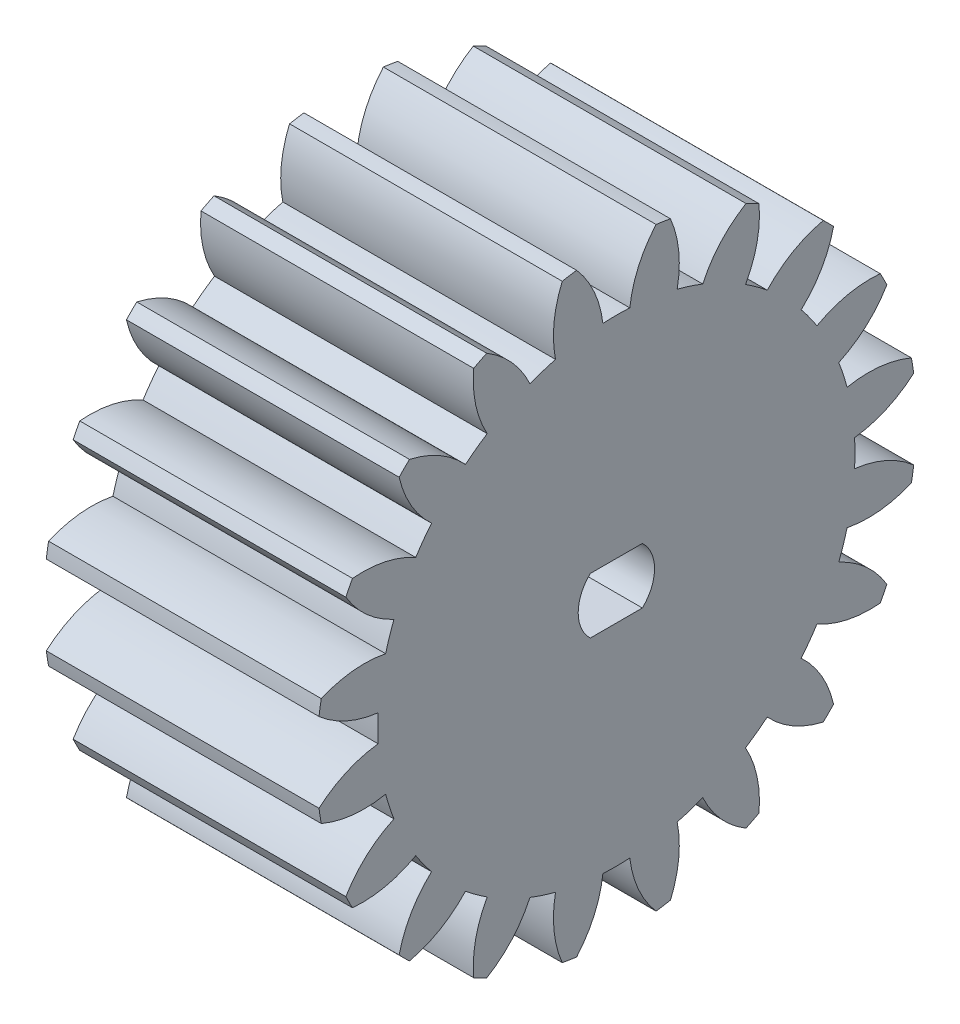
SolidWorks part; units mm, degrees
material "Delrin 2700 NC010, Low Viscosity Acetal Copolymer (SS)"
ref_plane "Plane1" through (0, 0, 0) normal (0, 0, 1) x (1, 0, 0)
ref_plane "Plane2" through (0, 0, 0) normal (0, 1, 0) x (1, 0, 0)
ref_plane "Plane3" through (0, 0, 0) normal (1, 0, 0) x (0, 0, -1)
sketch "HoldingSke" plane through (0, 0, 0) normal (0, 1, 0) x (1, 0, 0)
  line L0 (0, 0) -> (0.4698, -0.171)
  line L1 (-15, 0) -> (100, 0) construction
  line L2 (0, 0) -> (-2.1039, 2.3779)
  line L3 (0, 0) -> (-11.863, 4.5341)
  line L4 (0, 0) -> (8.1152, 2.9537)
  line L5 (0, 0) -> (-46.8476, -17.4728)
  line L6 (0, 0) -> (-4.1448, -2.7965)
  line L7 (-2.1039, 2.3779) -> (8.6586, 51.2059)
  line L8 (-76.2, 54.61) -> (-76.1, 54.61)
  line L9 (-71.009, 38.7566) -> (-53.1078, 45.2721)
  line L10 (-76.2, 71.12) -> (104.1128, 71.12)
  line L11 (0, 0) -> (-5, 0)
  line L12 (-76.2, 101.6) -> (-76.133, 101.6)
  line L13 (24.9733, 27.94) -> (52.9518, 28.4284)
  line L14 (24.9733, 27.94) -> (24.9743, 27.94)
  line L15 (24.9733, 27.94) -> (100.4006, 29.5858)
  line L16 (-63.627, -2) -> (-12.827, -2)
  circle A0 centre (0, 0) radius 0.4
  circle A1 centre (0, 0) radius 17.499
  circle A2 centre (0, 0) radius 37.5
  circle A3 centre (0, 0) radius 0.4
  dimension "MHD" = 34.998
  dimension "Hub_dia" = 75
  dimension "Bore" = 0.8
  dimension "MBD" = 0.8
  dimension "Num_teeth" = 20
  dimension "Pitch" = 0.5
  dimension "Overall_len" = 50
  dimension "Show_teeth" = 20
  dimension "Thickness" = 5
  dimension "OAL" = 50.0001
  dimension "T_dim" = 0.1
  dimension "Ap" = 20
  dimension "H" = 19.05
  dimension "Pitch_radius" = 180.3128
  dimension "Width" = 5
  dimension "Backlash" = 0.067
  dimension "Addendum_fac" = 1
  dimension "Dedendum_fac" = 1.25
  dimension "Clearance_fac" = 0.25
  dimension "Dedendum_add" = 0.001
  dimension "Module" = 2
sketch "BasProSke" plane through (0, 0, 0) normal (0, 1, 0) x (1, 0, 0)
  line L0 (-10, 0) -> (60, 0) construction
  line L1 (0, 0) -> (0, 22)
  line L2 (0, 0) -> (20, 0)
  line L3 (20, 0) -> (20, 22)
  line L4 (20, 22) -> (0, 22)
  dimension "Thickness" = 20
  dimension "Diameter" = 44
revolve "Base-Revolve" add sketch "BasProSke" angle 360 about L0
sketch "TooCutSke" plane through (0, 0, 0) normal (1, 0, 0) x (0, 0, -1)
  line L1 (0, 0) -> (0, 107) construction
  line L2 (0, 0) -> (-1.6864, 19.9288) construction
  line L3 (0, 0) -> (-6.2409, 39.4033) construction
  line L4 (-1.6864, 19.9288) -> (-3.1204, 19.7016) construction
  arc A0 (0.9862, 17.4712) -> (-0.9862, 17.4712) centre (0, 0) ccw
  arc A1 (2.9329, 21.8293) -> (-2.9329, 21.8293) centre (0, 0) ccw
  circle A2 centre (0, 0) radius 20 construction
  circle A3 centre (0, 0) radius 18.7939 construction
  arc A4 (-0.9862, 17.4712) -> (-2.9329, 21.8293) centre (-8.9313, 16.536) ccw
  arc A5 (2.9329, 21.8293) -> (0.9862, 17.4712) centre (8.9313, 16.536) ccw
  dimension "Root_dia" = 34.998
  dimension "Overcut_dia" = 44.0508
  dimension "Pitch_dia" = 40
  dimension "Base_dia" = 37.5877
  dimension "Flank_rad" = 8
  dimension "Half_ang" = 9
  dimension "Half_CT" = 1.4519
extrude "ToothCut" cut sketch "TooCutSke" along normal through all
fillet "Breaks" [suppressed] radius 0.04
fillet "RootFillets" [suppressed] radius 0.501
pattern_circular "TeethCuts" count 20 every 18 about axis through (-10, 0, 0) along (1, 0, 0) of "ToothCut", "RootFillets", "Breaks"
sketch "HubNeaOneSke" plane through (0, 0, 0) normal (-1, 0, 0) x (0, 0, 1)
  circle A0 centre (0, 0) radius 17.499
  dimension "Diameter" = 34.998
extrude "HubNearOne" [suppressed] add sketch "HubNeaOneSke" along normal blind 30.0001
sketch "HubNeaBotSke" plane through (0, 0, 0) normal (-1, 0, 0) x (0, 0, 1)
  circle A0 centre (0, 0) radius 17.499
  dimension "Diameter" = 34.998
extrude "HubNearBoth" [suppressed] add sketch "HubNeaBotSke" along normal blind 15
ref_plane "FarPln" through (20, 0, 0) normal (1, 0, 0) x (0, 0, -1)
sketch "HubFarSke" plane through (20, 0, 0) normal (1, 0, 0) x (0, 0, -1)
  circle A0 centre (0, 0) radius 17.499
  dimension "Diameter" = 34.998
extrude "HubFar" [suppressed] add sketch "HubFarSke" along normal blind 15
sketch "BorSke" plane through (0, 0, 0) normal (1, 0, 0) x (0, 0, -1)
  circle A0 centre (0, 0) radius 0.4
  dimension "Diameter" = 0.8
extrude "Bore" [suppressed] cut sketch "BorSke" along normal mid plane 100.0001
sketch "KeySke" plane through (0, 0, 0) normal (1, 0, 0) x (0, 0, -1)
  line L0 (-0.05, 0) -> (-0.05, 0.5)
  line L1 (-0.05, 0.5) -> (0.05, 0.5)
  line L2 (0.05, 0.5) -> (0.05, 0)
  line L3 (0, 0) -> (0, 34) construction
  line L4 (-0.05, 0) -> (0.05, 0)
  dimension "Offset" = 0.5
  dimension "Width" = 0.1
extrude "Keyway" [suppressed] cut sketch "KeySke" along normal mid plane 100.0001
pattern_circular "Keyway2" [suppressed] count 2 every 90 about axis through (-10, 0, 0) along (1, 0, 0)
sketch "Sketch1" plane through (20, 0, 0) normal (1, 0, 0) x (0, 0, -1)
  line L0 (-1.9072, 2.05) -> (1.9072, 2.05)
  line L1 (-1.9072, -2.05) -> (1.9072, -2.05)
  circle A0 centre (0, 0) radius 2.8
  dimension "D1" = 5.6
  dimension "D2" = 2.05
  dimension "D3" = 2.05
extrude "Cut-Extrude1" cut sketch "Sketch1" against normal through all contours L0 A0 L1
equation "' \"Module@HoldingSke\" = 6.35"
equation "' \"Num_teeth@HoldingSke\" = 12"
equation "' \"Ap@HoldingSke\" =  20"
equation "' \"Ap@HoldingSke\" = 20"
equation "' \"Width@HoldingSke\" = 0.5 * 25.4"
equation "' \"Hub_dia@HoldingSke\"= 1 * 25.4"
equation "' \"Hub_dia@HoldingSke\" = 1 * 25.4"
equation "' \"Overall_len@HoldingSke\" = 1.0 * 25.4"
equation "' \"Bore@HoldingSke\" = 0.75 * 25.4"
equation "' \"T_dim@HoldingSke\" = 0.1 * 25.4"
equation "' \"Width@KeySke\" = 0.25 * 25.4"
equation "' \"Show_teeth@HoldingSke\" = 13"
equation "' \"Backlash@HoldingSke\" = 0.009 * 25.4"
equation "' \"Addendum_fac@HoldingSke\" = 1.0"
equation "' \"Dedendum_fac@HoldingSke\" = 1.25"
equation "' \"Dedendum_add@HoldingSke\" = 0.00005 * 25.4"
equation "' \"Clearance_fac@HoldingSke\" = 0.25"
equation "\"Pitch@HoldingSke\" = 1 / \"Module@HoldingSke\""
equation "\"Overcut_dia@TooCutSke\" = (\"Num_teeth@HoldingSke\" + 2 * \"Addendum_fac@HoldingSke\") / \"Pitch@HoldingSke\" + 0.002 * 25.4"
equation "\"Pitch_dia@TooCutSke\" = \"Num_teeth@HoldingSke\" / \"Pitch@HoldingSke\""
equation "\"Base_dia@TooCutSke\" = \"Num_teeth@HoldingSke\" / \"Pitch@HoldingSke\" * cos((\"Ap@HoldingSke\"  * 3.14159265 / 180))"
equation "\"Root_dia@TooCutSke\" = (\"Num_teeth@HoldingSke\" + 2) / \"Pitch@HoldingSke\" - 2 * (\"Addendum_fac@HoldingSke\" + \"Dedendum_fac@HoldingSke\") / \"Pitch@HoldingSke\" - \"Dedendum_add@HoldingSke\" * 2"
equation "\"Half_ang@TooCutSke\" = 180 / \"Num_teeth@HoldingSke\""
equation "\"Half_CT@TooCutSke\" = \"Num_teeth@HoldingSke\" / \"Pitch@HoldingSke\" * sin((3.14159265 / 2 / \"Num_teeth@HoldingSke\")) / 2 - 7 * \"Backlash@HoldingSke\" / 4"
equation "\"Flank_rad@TooCutSke\" = \"Num_teeth@HoldingSke\" / \"Pitch@HoldingSke\" / 5"
equation "\"Radius@RootFillets\" = \"Clearance_fac@HoldingSke\" / \"Pitch@HoldingSke\" + \"Dedendum_add@HoldingSke\""
equation "\"Break_rad@Breaks\" = 0.02 / \"Pitch@HoldingSke\""
equation "\"Thickness@HoldingSke\" = \"Width@HoldingSke\""
equation "\"OAL@HoldingSke\" = \"Thickness@HoldingSke\""
equation "\"MHD@HoldingSke\" = (\"Num_teeth@HoldingSke\" + 2) / \"Pitch@HoldingSke\" - 2 * (\"Addendum_fac@HoldingSke\" + \"Dedendum_fac@HoldingSke\")  / \"Pitch@HoldingSke\" - \"Dedendum_add@HoldingSke\" * 2"
equation "\"MBD@HoldingSke\" = (\"Num_teeth@HoldingSke\" + 2) / \"Pitch@HoldingSke\" - 2 * (\"Addendum_fac@HoldingSke\" + \"Dedendum_fac@HoldingSke\")  / \"Pitch@HoldingSke\" - \"Dedendum_add@HoldingSke\" * 2 - 0.002 * 25.4"
equation "\"MHD@HoldingSke\" = ((sgn( \"MHD@HoldingSke\" - \"Hub_dia@HoldingSke\" )-1)*( \"MHD@HoldingSke\" - \"Hub_dia@HoldingSke\" ))/-2+ \"Hub_dia@HoldingSke\""
equation "\"MBD@HoldingSke\" = ((sgn( \"MBD@HoldingSke\" - \"Bore@HoldingSke\" )-1)*( \"MBD@HoldingSke\" - \"Bore@HoldingSke\" ))/-2+ \"Bore@HoldingSke\""
equation "\"OAL@HoldingSke\" = ((sgn( \"OAL@HoldingSke\" - \"Overall_len@HoldingSke\" )+1)*( \"OAL@HoldingSke\" - \"Overall_len@HoldingSke\" ))/2 + \"Overall_len@HoldingSke\" + 0.000002 * 25.4"
equation "\"Num_teeth@TeethCuts\" = int( \"Show_teeth@HoldingSke\" ) + 1"
equation "\"Num_teeth@TeethCuts\" = ((sgn( \"Num_teeth@TeethCuts\" - \"Num_teeth@HoldingSke\" )-1)*( \"Num_teeth@TeethCuts\" - \"Num_teeth@HoldingSke\" ))/-2+ \"Num_teeth@HoldingSke\""
equation "\"Num_teeth@TeethCuts\" = ((sgn( \"Num_teeth@TeethCuts\" - 2.0)+1)*( \"Num_teeth@TeethCuts\" - 2.0))/2 +2.0"
equation "\"Angle@TeethCuts\" = 360.0 / \"Num_teeth@HoldingSke\""
equation "\"Diameter@BasProSke\" = (\"Num_teeth@HoldingSke\" + 2 * \"Addendum_fac@HoldingSke\") / \"Pitch@HoldingSke\""
equation "' \"Fillet_rad@BasProSke\" =  \"Thickness@HoldingSke\" * 0.05"
equation "' \"Fillet_rad@BasProSke\" = \"Thickness@HoldingSke\" * 0.05"
equation "\"MHD@HoldingSke\" = ((sgn( \"MHD@HoldingSke\" - \"Root_dia@TooCutSke\" )-1)*( \"MHD@HoldingSke\" - \"Root_dia@TooCutSke\" ))/-2+ \"Root_dia@TooCutSke\""
equation "\"Diameter@HubNeaOneSke\" = \"MHD@HoldingSke\""
equation "\"Length@HubNearOne\" = \"OAL@HoldingSke\" - \"Thickness@BasProSke\""
equation "\"Diameter@HubNeaBotSke\" = \"MHD@HoldingSke\""
equation "\"Length@HubNearBoth\" = ( \"OAL@HoldingSke\" - \"Thickness@BasProSke\" ) / 2.0"
equation "\"Thickness@FarPln\" = \"Thickness@BasProSke\""
equation "\"Diameter@HubFarSke\" = \"MHD@HoldingSke\""
equation "\"Length@HubFar\" = ( \"OAL@HoldingSke\" - \"Thickness@BasProSke\" ) / 2.0"
equation "\"Diameter@BorSke\" = \"MBD@HoldingSke\""
equation "\"D1@Bore\" = \"OAL@HoldingSke\" * 2.0"
equation "\"D1@Keyway\" = \"OAL@HoldingSke\" * 2.0"
equation "\"Offset@KeySke\" = \"T_dim@HoldingSke\" + \"MBD@HoldingSke\" / 2.0"
